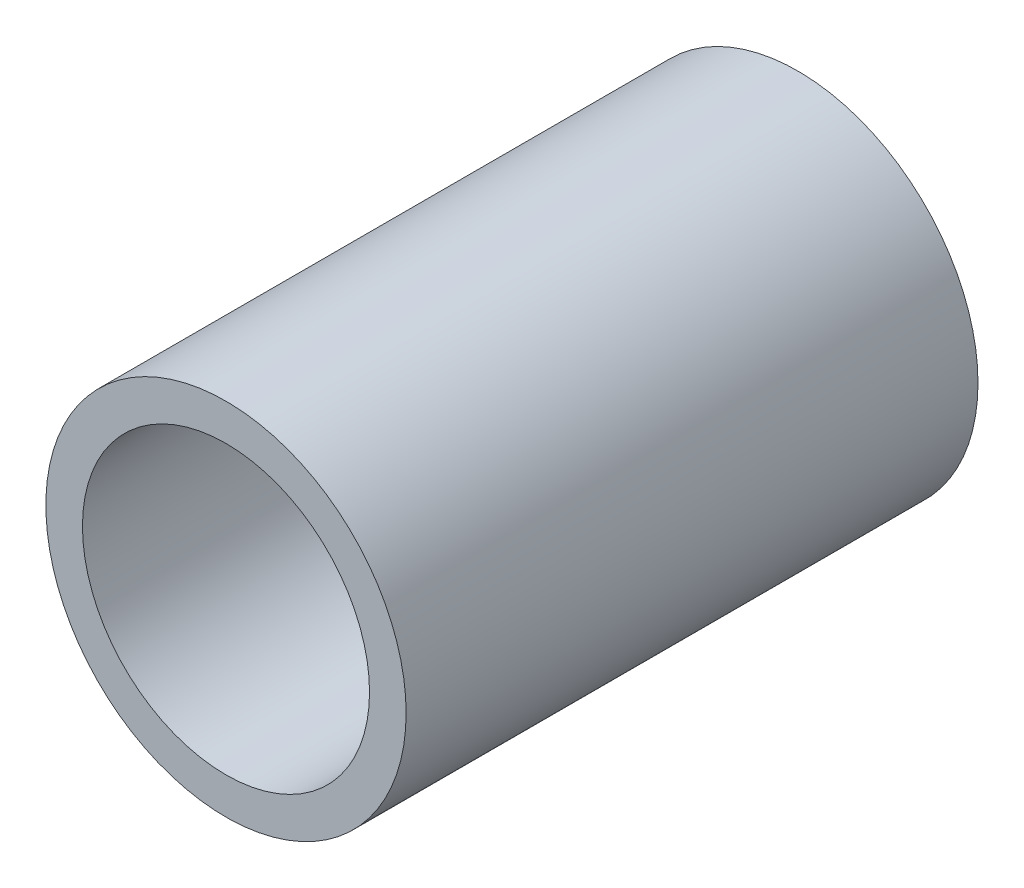
SolidWorks part; units mm, degrees
material "Commercial Bronze, UNS C22000 (90-10 Bronze)"
ref_plane "Front Plane" through (0, 0, 0) normal (0, 0, 1) x (1, 0, 0)
ref_plane "Top Plane" through (0, 0, 0) normal (0, 1, 0) x (1, 0, 0)
ref_plane "Right Plane" through (0, 0, 0) normal (1, 0, 0) x (0, 0, -1)
sketch "Sketch1" plane through (0, 0, 0) normal (0, 0, 1) x (1, 0, 0)
  circle A0 centre (0, 0) radius 4.0005
  circle A1 centre (0, 0) radius 3.1877
  dimension "ID" = 6.3754
  dimension "OD" = 8.001
extrude "Boss-Extrude1" add sketch "Sketch1" along normal mid plane 12.7
sketch "Sketch2" plane through (0, 0, 0) normal (1, 0, 0) x (0, 0, -1)
  line L0 (-6.35, 4.0005) -> (6.35, 4.0005)
  line L1 (-6.35, 0) -> (6.35, 0) construction
  line L2 (-6.35, 4.0005) -> (-6.35, -4.0005) construction
  line L3 (6.35, -4.0005) -> (6.35, 4.0005) construction
  dimension "D1" = 8.001
  dimension "D2" = 12.7
equation "\"D1@Sketch2\"=\"OD@Sketch1\""
